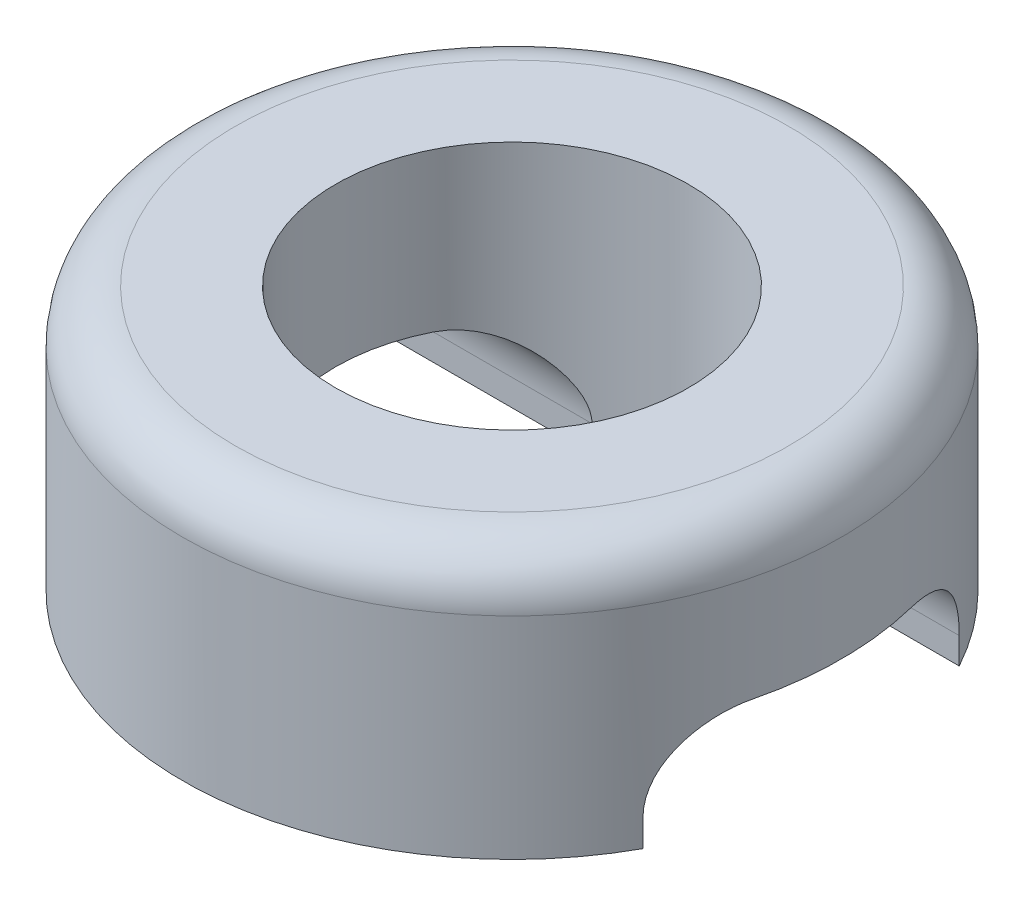
SolidWorks part; units mm, degrees
ref_plane "Front Plane" through (0, 0, 0) normal (0, 0, 1) x (1, 0, 0)
ref_plane "Top Plane" through (0, 0, 0) normal (0, 1, 0) x (1, 0, 0)
ref_plane "Right Plane" through (0, 0, 0) normal (1, 0, 0) x (0, 0, -1)
sketch "Sketch1" plane through (0, 0, 0) normal (0, 1, 0) x (1, 0, 0)
  circle A0 centre (0, 0) radius 4.25
  circle A1 centre (0, 0) radius 7.9375
  dimension "D1" = 8.5
  dimension "D2" = 15.875
extrude "Boss-Extrude1" add sketch "Sketch1" along normal blind 6.35
sketch "Sketch2" plane through (0, 0, 0) normal (1, 0, 0) x (0, 0, -1)
  line L5 (-7.9375, 0) -> (7.9375, 0) construction
  line L6 (3.81, 0) -> (-3.81, 0)
  line L7 (0, 0) -> (0, 2.54) construction
  line L8 (3.81, 2.54) -> (-3.81, 2.54)
  line L9 (3.81, 2.54) -> (3.81, 0)
  line L10 (-3.81, 2.54) -> (-3.81, 0)
  point P16 (0, 0)
  point P22 (0, 2.54)
  dimension "D5" = 7.62
  dimension "D6" = 2.54
extrude "Cut-Extrude1" cut sketch "Sketch2" against normal through all and the other way through all
fillet "Fillet2" radius 1.905 4 edges at (4.4233, 2.54, -3.81) (-4.4233, 2.54, -3.81) (-4.4233, 2.54, 3.81) (4.4233, 2.54, 3.81)
fillet "Fillet3" radius 1.27 1 edges at (0, 6.35, 7.9375)
